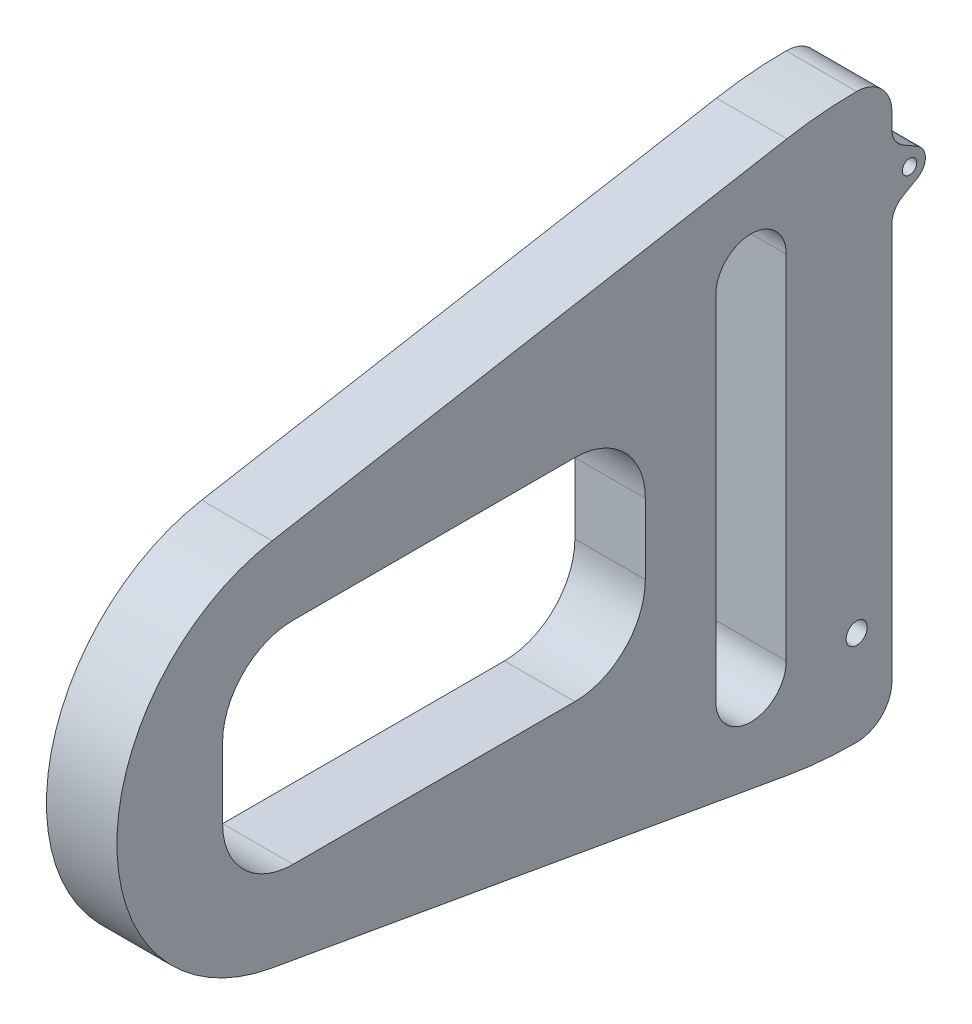
SolidWorks part; units mm, degrees
ref_plane "Plan de face" through (0, 0, 0) normal (0, 0, 1) x (1, 0, 0)
ref_plane "Plan de dessus" through (0, 0, 0) normal (0, 1, 0) x (1, 0, 0)
ref_plane "Plan de droite" through (0, 0, 0) normal (1, 0, 0) x (0, 0, -1)
sketch "Esquisse1" plane through (0, 0, 0) normal (0, 0, 1) x (1, 0, 0)
  line L1 (-5, 40) -> (5, 40)
  line L2 (-5, 40) -> (-5, -40)
  line L3 (-5, -40) -> (5, -40)
  line L4 (5, 40) -> (5, -40)
  line L5 (-5, 40) -> (5, -40) construction
  line L6 (-5, -40) -> (5, 40) construction
  point P0 (0, 0)
  dimension "D1" = 80
  dimension "D2" = 10
extrude "Boss.-Extru.1" add sketch "Esquisse1" along normal blind 10
sketch "Esquisse2" plane through (-5, 0, 0) normal (-1, 0, 0) x (0, 0, 1)
  line L0 (10, 40) -> (110, 22.3673)
  line L1 (0, 0) -> (110.0662, 0) construction
  line L2 (10, 40) -> (10, -40) construction
  line L3 (10, -40) -> (110, -22.3673)
  line L4 (110, 22.3673) -> (110, -22.3673)
  line L5 (10, 40) -> (10, -40)
  line L6 (20, 25) -> (20, -25) construction
  line L7 (25, 25) -> (25, -25)
  line L8 (15, 25) -> (15, -25)
  line L10 (45, 15) -> (85, 15)
  line L11 (35, 5) -> (35, -5)
  line L12 (45, -15) -> (85, -15)
  line L13 (95, 5) -> (95, -5)
  line L14 (35, 15) -> (95, -15) construction
  line L15 (35, -15) -> (95, 15) construction
  arc A0 (25, 25) -> (15, 25) centre (20, 25) ccw
  arc A1 (15, -25) -> (25, -25) centre (20, -25) ccw
  arc A2 (85, -15) -> (95, -5) centre (85, -5) ccw
  arc A3 (35, -5) -> (45, -15) centre (45, -5) ccw
  arc A4 (45, 15) -> (35, 5) centre (45, 5) ccw
  arc A5 (85, 15) -> (95, 5) centre (85, 5) cw
  point P2 (65, 0)
  point P10 (20, 0)
  dimension "D4" = 5
  dimension "D9" = 10
  dimension "D1" = 100
  dimension "D2" = 80
  dimension "D3" = 50
  dimension "D5" = 10
  dimension "D6" = 30
  dimension "D7" = 60
  dimension "D8" = 55
extrude "Boss.-Extru.2" add sketch "Esquisse2" against normal through all
fillet "Congé1" radius 26.6563 4 edges at (5, 0, 110) (0, 22.3673, 110) (0, -22.3673, 110) (-5, 0, 110)
sketch "Esquisse4" plane through (5, 0, 0) normal (1, 0, 0) x (0, 0, -1)
  circle A0 centre (-5, -26.5787) radius 1.5
extrude "Enlèv. mat.-Extru.2" cut sketch "Esquisse4" against normal through all
sketch "Esquisse7" plane through (5, 0, 0) normal (1, 0, 0) x (0, 0, -1)
  line L0 (3.625, 28.9486) -> (0, 31.0415)
  line L1 (0, -40) -> (0, 40) construction
  line L2 (-1.7242, 27) -> (6.7242, 27) construction
  line L3 (3.625, 25.0514) -> (0, 22.9585)
  line L4 (0, 22.9585) -> (0, 31.0415)
  circle A0 centre (2.5, 27) radius 1.025
  arc A1 (3.625, 25.0514) -> (3.625, 28.9486) centre (2.5, 27) ccw
  point P11 (2.5, 27)
  dimension "D1" = 4.5
  dimension "D2" = 2.05
  dimension "D3" = 60
extrude "Boss.-Extru.3" add sketch "Esquisse7" against normal through all
fillet "Congé2" radius 3 1 edges at (0, 22.9585, 0)
fillet "Congé3" radius 3 1 edges at (0, 31.0415, 0)
fillet "Congé4" radius 5 2 edges at (0, -40, 0) (0, 40, 0)
fillet "Congé5" radius 57 1 edges at (0, 40, 10)
fillet "Congé6" radius 57 1 edges at (0, -40, 10)
sketch "Esquisse8" plane through (-5, 0, 0) normal (-1, 0, 0) x (0, 0, 1)
  line L4 (95, -5) -> (95, 5) construction
  line L5 (45, -15) -> (85, -15) construction
  line L6 (35, 5) -> (35, -5) construction
  line L7 (85, 15) -> (45, 15) construction
  line L8 (95, -5) -> (95, 5)
  line L9 (45, -15) -> (85, -15)
  line L10 (35, 5) -> (35, -5)
  line L11 (85, 15) -> (45, 15)
  arc A4 (95, 5) -> (85, 15) centre (85, 5) ccw construction
  arc A5 (85, -15) -> (95, -5) centre (85, -5) ccw construction
  arc A6 (35, -5) -> (45, -15) centre (45, -5) ccw construction
  arc A7 (45, 15) -> (35, 5) centre (45, 5) ccw construction
  arc A8 (95, 5) -> (85, 15) centre (85, 5) ccw
  arc A9 (85, -15) -> (95, -5) centre (85, -5) ccw
  arc A10 (35, -5) -> (45, -15) centre (45, -5) ccw
  arc A11 (45, 15) -> (35, 5) centre (45, 5) ccw
